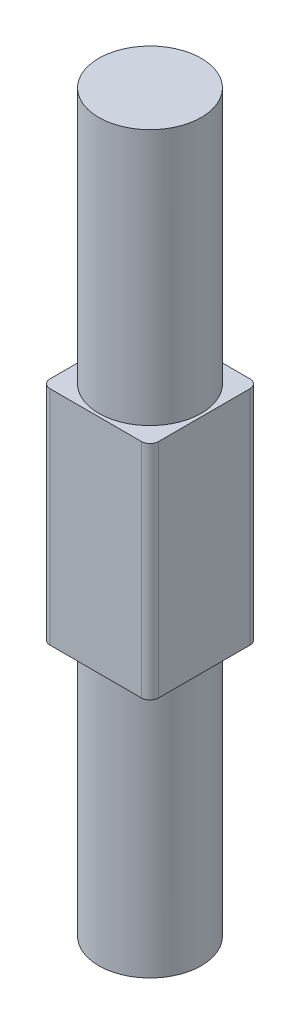
SolidWorks part; units mm, degrees
ref_plane "Plan de face" through (0, 0, 0) normal (0, 0, 1) x (1, 0, 0)
ref_plane "Plan de dessus" through (0, 0, 0) normal (0, 1, 0) x (1, 0, 0)
ref_plane "Plan de droite" through (0, 0, 0) normal (1, 0, 0) x (0, 0, -1)
sketch "Esquisse1" plane through (0, 0, 0) normal (0, 1, 0) x (1, 0, 0)
  line L1 (0, 0) -> (6.35, 0)
  line L2 (0, 0) -> (0, 6.35)
  line L3 (0, 6.35) -> (6.35, 6.35)
  line L4 (6.35, 0) -> (6.35, 6.35)
  dimension "D1" = 6.35
extrude "Boss.-Extru.1" add sketch "Esquisse1" along normal blind 13
sketch "Esquisse2" plane through (0, 13, 0) normal (0, 1, 0) x (1, 0, 0)
  line L0 (0, 0) -> (6.35, 6.35) construction
  line L1 (6.35, 0) -> (0, 6.35) construction
  circle A0 centre (3.175, 3.175) radius 3
  dimension "D1" = 6
extrude "Boss.-Extru.2" add sketch "Esquisse2" along normal blind 15 and the other way blind 28
fillet "Congé1" radius 0.5 4 edges at (0, 6.5, 0) (6.35, 6.5, 0) (0, 6.5, -6.35) (6.35, 6.5, -6.35)
